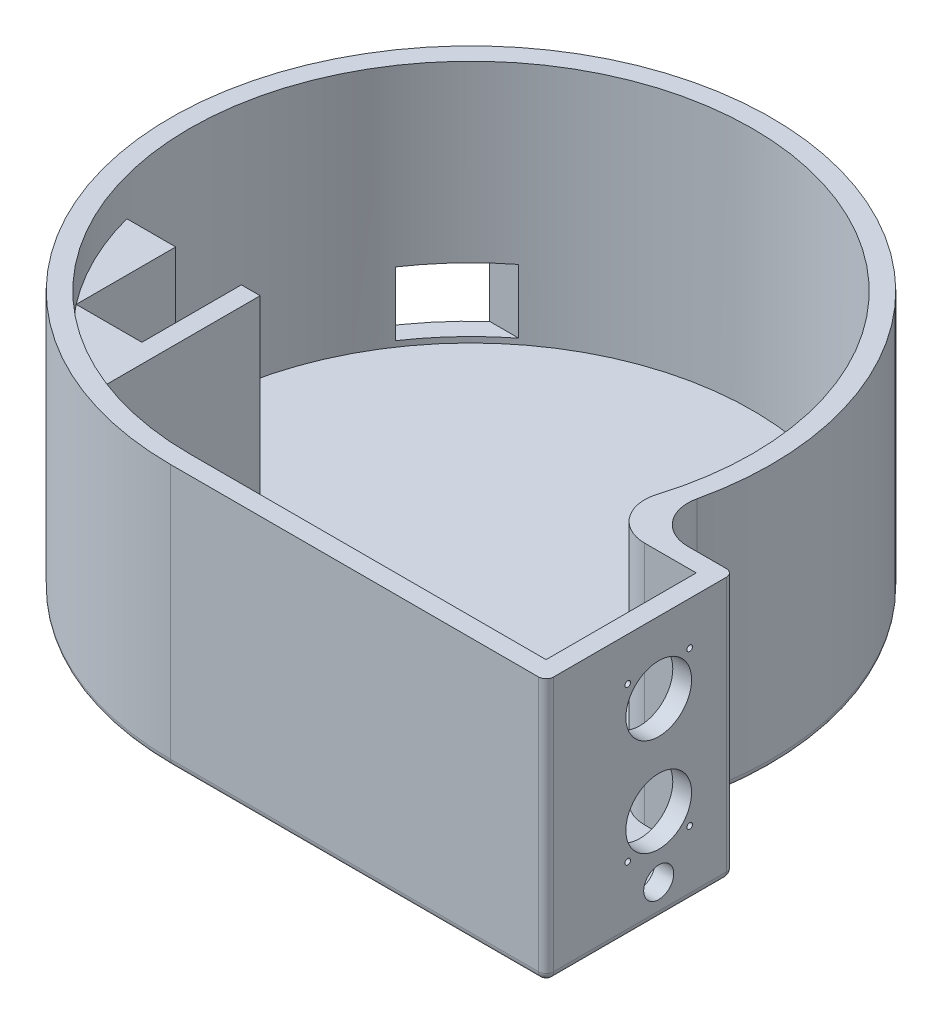
SolidWorks part; units mm, degrees
ref_plane "Front Plane" through (0, 0, 0) normal (0, 0, 1) x (1, 0, 0)
ref_plane "Top Plane" through (0, 0, 0) normal (0, 1, 0) x (1, 0, 0)
ref_plane "Right Plane" through (0, 0, 0) normal (1, 0, 0) x (0, 0, -1)
sketch "Sketch1" plane through (0, 0, 0) normal (0, 1, 0) x (1, 0, 0)
  line L0 (0, -80) -> (100, -80)
  line L1 (100, -80) -> (100, -30)
  line L2 (100, -30) -> (74.162, -30)
  arc A0 (74.162, -30) -> (0, -80) centre (0, 0) ccw
  dimension "D1" = 160
  dimension "D2" = 100
  dimension "D3" = 50
  dimension "D4" = 100
extrude "Boss-Extrude1" add sketch "Sketch1" along normal blind 70
shell "Shell1" thickness 5
sketch "Sketch2" plane through (0, 0, 0) normal (0, 1, 0) x (1, 0, 0)
  line L1 (-107.5, -102.5) -> (107.5, -102.5)
  line L2 (-107.5, -102.5) -> (-107.5, 102.5)
  line L3 (-107.5, 102.5) -> (107.5, 102.5)
  line L4 (107.5, -102.5) -> (107.5, 102.5)
  line L5 (-107.5, -102.5) -> (107.5, 102.5) construction
  line L6 (-107.5, 102.5) -> (107.5, -102.5) construction
  point P0 (0, 0)
  dimension "D1" = 215
  dimension "D2" = 205
extrude "Boss-Extrude2" [suppressed] add sketch "Sketch2" along normal blind 215 separate body
sketch "Sketch3" plane through (100, 0, 0) normal (1, 0, 0) x (0, 0, -1)
  line L0 (-50, 25) -> (-50, 51) construction
  line L1 (-41.75, 58.5) -> (-41.75, 17.5) construction
  line L2 (-41.75, 17.5) -> (-58.25, 17.5) construction
  line L3 (-58.25, 17.5) -> (-58.25, 58.5) construction
  line L4 (-58.25, 58.5) -> (-41.75, 58.5) construction
  line L5 (-50, 58.5) -> (-50, 17.5) construction
  line L8 (-30, 70) -> (-30, 0) construction
  line L9 (-80, 0) -> (-30, 0) construction
  line L10 (-50, 8.65) -> (-50, 25) construction
  circle A0 centre (-50, 25) radius 8.75
  circle A1 centre (-50, 51) radius 8.75
  circle A2 centre (-41.75, 58.5) radius 0.75
  circle A3 centre (-41.75, 17.5) radius 0.75
  circle A4 centre (-58.25, 17.5) radius 0.75
  circle A5 centre (-58.25, 58.5) radius 0.75
  circle A6 centre (-50, 8.65) radius 4
  point P12 (-50, 38)
  point P15 (-50, 38)
  dimension "D1" = 17.5
  dimension "D2" = 17.5
  dimension "D4" = 1.5
  dimension "D10" = 8
  dimension "D3" = 26
  dimension "D5" = 41
  dimension "D6" = 16.5
  dimension "D7" = 25
  dimension "D8" = 20
  dimension "D9" = 16.35
extrude "Cut-Extrude1" cut sketch "Sketch3" against normal up to surface (5 mm away) up to face at (95, 37.5, 55)
sketch "Sketch4" plane through (0, 0, 0) normal (1, 0, 0) x (0, 0, -1)
  line L0 (-80, 0) -> (80, 0) construction
  line L1 (59, 6.5) -> (42, 6.5)
  line L2 (59, 6.5) -> (59, 23.5)
  line L3 (59, 23.5) -> (42, 23.5)
  line L4 (42, 6.5) -> (42, 23.5)
  line L5 (59, 6.5) -> (42, 23.5) construction
  line L6 (59, 23.5) -> (42, 6.5) construction
  line L8 (0, 70) -> (0, 0) construction
  line L9 (-10.5, 8.5) -> (10.5, 8.5)
  line L10 (-10.5, 8.5) -> (-10.5, 21.5)
  line L11 (-10.5, 21.5) -> (10.5, 21.5)
  line L12 (10.5, 8.5) -> (10.5, 21.5)
  line L13 (-10.5, 8.5) -> (10.5, 21.5) construction
  line L14 (-10.5, 21.5) -> (10.5, 8.5) construction
  line L15 (0, 15) -> (50.5, 15) construction
  point P0 (50.5, 15)
  point P5 (0, 15)
  dimension "D4" = 13
  dimension "D1" = 15
  dimension "D2" = 17
  dimension "D3" = 17
  dimension "D5" = 21
  dimension "D6" = 42
extrude "Cut-Extrude2" cut sketch "Sketch4" against normal up to surface (68.0882 mm away)
sketch "Sketch5" plane through (0, 0, 0) normal (0, 0, 1) x (1, 0, 0)
  line L5 (-79.9967, 8.5) -> (-80, 21.5) construction
  line L6 (-79.3079, 8.5) -> (-80, 8.5) construction
  line L8 (-81.2483, 6) -> (-78.7483, 6)
  line L9 (-81.2483, 6) -> (-81.2483, 24)
  line L10 (-81.2483, 24) -> (-78.7483, 24)
  line L11 (-78.7483, 6) -> (-78.7483, 24)
  line L12 (-81.2483, 6) -> (-78.7483, 24) construction
  line L13 (-81.2483, 24) -> (-78.7483, 6) construction
  point P4 (-79.9983, 15)
  dimension "D1" = 2.5
  dimension "D2" = 18
extrude "Cut-Extrude3" cut sketch "Sketch5" against normal through all both and the other way through all
sketch "Sketch6" plane through (0, 5, 0) normal (0, 1, 0) x (1, 0, 0)
  line L1 (-72.5177, -19.136) -> (-59.5177, -19.136)
  line L2 (-59.5177, -19.136) -> (-59.5177, -45.636)
  line L3 (-42.0177, -45.636) -> (-42.0177, -19.136)
  line L4 (-42.0177, -19.136) -> (-37.0177, -19.136)
  line L5 (-37.0177, -19.136) -> (-37.0177, -65.228)
  line L6 (-72.5177, -19.136) -> (-59.5177, -19.136) construction
  line L7 (-59.5177, -45.636) -> (-42.0177, -45.636) construction
  line L8 (-59.5177, -45.636) -> (-42.0177, -45.636)
  line L13 (-37.0177, -67.228) -> (-37.0177, -65.228)
  line L14 (-72.5177, -19.136) -> (-74.5177, -19.136)
  arc A0 (66.3325, -35) -> (0, -75) centre (0, 0) ccw construction
  arc A1 (66.3325, -35) -> (0, -75) centre (0, 0) ccw construction
  arc A4 (-74.5177, -19.136) -> (-37.0177, -67.228) centre (-6.0785, -4.4366) ccw
  dimension "D7" = 70
  dimension "D1" = 5
  dimension "D2" = 13
  dimension "D3" = 26.5
  dimension "D4" = 17.5
  dimension "D5" = 2
  dimension "D6" = 2
extrude "Boss-Extrude3" add sketch "Sketch6" along normal blind 55
fillet "Fillet1" radius 10 2 edges at (74.162, 35, 30) (66.3325, 37.5, 35)
fillet "Fillet2" radius 2 7 edges at (93.8748, 0, 30) (79.9323, 0, 26.2361) (50, 0, 80) (100, 35, 80) (100, 35, 30) (100, 0, 55) (-49.8888, 0, -62.5389)
